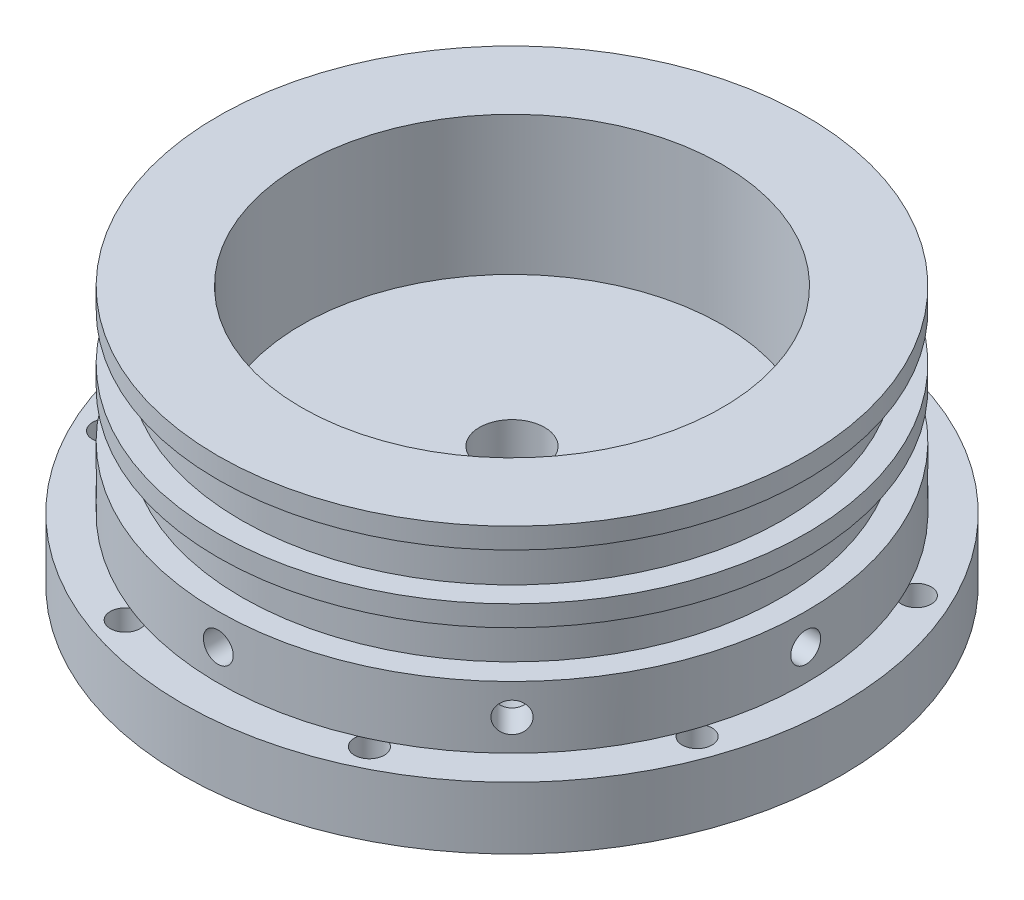
SolidWorks part; units mm, degrees
material "Nylon 101"
ref_plane "Front Plane" through (0, 0, 0) normal (0, 0, 1) x (1, 0, 0)
ref_plane "Top Plane" through (0, 0, 0) normal (0, 1, 0) x (1, 0, 0)
ref_plane "Right Plane" through (0, 0, 0) normal (1, 0, 0) x (0, 0, -1)
sketch "Sketch1" plane through (0, 0, 0) normal (0, 1, 0) x (1, 0, 0)
  circle A0 centre (0, 0) radius 45.085
  dimension "D1" = 90.17
extrude "Boss-Extrude1" add sketch "Sketch1" along normal blind 9.525
sketch "Sketch2" plane through (0, 9.525, 0) normal (0, 1, 0) x (1, 0, 0)
  circle A0 centre (0, 0) radius 41.402
  dimension "D1" = 82.804
extrude "Boss-Extrude2" add sketch "Sketch2" along normal blind 7.1374
sketch "Sketch3" plane through (0, 16.6624, 0) normal (0, 1, 0) x (1, 0, 0)
  circle A0 centre (0, 0) radius 45.085
  dimension "D1" = 90.17
extrude "Boss-Extrude3" add sketch "Sketch3" along normal blind 3.175
sketch "Sketch4" plane through (0, 19.8374, 0) normal (0, 1, 0) x (1, 0, 0)
  circle A0 centre (0, 0) radius 41.529
  dimension "D1" = 83.058
extrude "Boss-Extrude4" add sketch "Sketch4" along normal blind 7.1374
sketch "Sketch5" plane through (0, 26.9748, 0) normal (0, 1, 0) x (1, 0, 0)
  circle A0 centre (0, 0) radius 45.085
  dimension "D1" = 90.17
extrude "Boss-Extrude5" add sketch "Sketch5" along normal blind 3.175
hole_wizard "#15 (0.18) Diameter Hole2" positions "3DSketch1" profile "Sketch6" hole size "#15" standard "ANSI Inch"
sketch3d "3DSketch1"
  line L0 (-45.085, 0, 0) -> (-45.085, 9.525, 0) construction
  circle A0 centre (0, 9.525, 0) radius 45.085 construction
  circle A1 centre (0, 0, 0) radius 45.085 construction
  point P0 (-45.085, 4.7625, 0)
  point P9 (0, 54.61, 0)
  point P14 (0, 45.085, 0)
sketch "Sketch6" plane through (-45.085, 4.7625, 0) normal (0, 1, 0) x (0, 0, 1)
  line L0 (0, 0) -> (0, 6.3736)
  line L1 (0, 6.3736) -> (2.286, 5)
  line L2 (2.286, 5) -> (2.286, 0)
  line L5 (2.286, 0) -> (0, 0)
  line L10 (0, 6.3736) -> (-2.286, 5) construction
  line L11 (0, -6.35) -> (0, 107.95) construction
  dimension "Hole Dia." = 4.572
  dimension "Hole Depth" = 5
  dimension "Drill Angle" = 118
pattern_circular "CirPattern1" count 8 over 360 about axis through (0, 9.525, 0) along (0, -1, 0) of "#15 (0.18) Diameter Hole2"
hole_wizard "M10x1.0 Tapped Hole1" positions "Sketch8" profile "Sketch7" tap size "M10x1.0" standard "ANSI Metric"
sketch "Sketch8" plane through (0, 0, 0) normal (0, -1, 0) x (-1, 0, 0)
  point P0 (0, 0)
sketch "Sketch7" plane through (0, 0, 0) normal (1, 0, 0) x (0, 0, -1)
  line L0 (0, 0) -> (0, 27.7039)
  line L1 (0, 27.7039) -> (4.5, 25)
  line L2 (4.5, 25) -> (4.5, 20)
  line L3 (4.5, 20) -> (5, 20)
  line L4 (5, 20) -> (5, 0)
  line L5 (5, 0) -> (0, 0)
  line L10 (0, 27.7039) -> (-4.5, 25) construction
  line L11 (0, -6.35) -> (0, 107.95) construction
  dimension "Tap Drill Dia." = 9
  dimension "Tap Drill Depth" = 25
  dimension "Thread Major Dia." = 10
  dimension "Thread Depth" = 20
  dimension "Drill Angle" = 118
sketch "Sketch9" plane through (0, 30.1498, 0) normal (0, 1, 0) x (1, 0, 0)
  circle A0 centre (0, 0) radius 40.259 construction
  circle A1 centre (0, 0) radius 32.259
  dimension "D1" = 80.518
  dimension "D2" = 8
extrude "Cut-Extrude1" cut sketch "Sketch9" against normal offset from surface (21.2598 mm away) 8.89 up to face at (0, 0, -5)
sketch "Sketch10" plane through (0, 0, 0) normal (0, -1, 0) x (1, 0, 0)
  line L0 (0, 0) -> (0, -32.385) construction
  line L1 (-6.35, -32.385) -> (6.35, -32.385)
  line L2 (-6.35, -32.385) -> (-6.35, -51.435)
  line L3 (-6.35, -51.435) -> (6.35, -51.435)
  line L4 (6.35, -32.385) -> (6.35, -51.435)
  circle A0 centre (0, 0) radius 45.085 construction
  point P9 (0, 0)
  dimension "D1" = 6.35
  dimension "D2" = 12.7
  dimension "D3" = 19.05
sketch "Sketch11" plane through (0, 0, 0) normal (0, -1, 0) x (-1, 0, 0)
  circle A0 centre (0, 0) radius 50.546
  dimension "D1" = 101.092
extrude "Boss-Extrude6" add sketch "Sketch11" along normal blind 9.525
sketch "Sketch12" plane through (0, -9.525, 0) normal (0, -1, 0) x (1, 0, 0)
  circle A0 centre (0, 0) radius 28.575
  dimension "D1" = 57.15
extrude "Cut-Extrude2" cut sketch "Sketch12" against normal up to surface (9.525 mm away) up to face at (0, 0, 45.085)
hole_wizard "#15 (0.18) Diameter Hole1" positions "3DSketch2" profile "Sketch15" hole size "#15" standard "ANSI Inch"
sketch3d "3DSketch2"
  line L0 (15.4596, -9.525, -43.8381) -> (0, 0, 0) construction
  line L2 (0, 0, 0) -> (0, 0, -44.5211) construction
  point P0 (15.4596, -9.525, -43.8381)
  dimension "D2" = 47.45
  dimension "D1" = 22.5
sketch "Sketch15" plane through (15.4596, -9.525, -43.8381) normal (1, 0, 0) x (0, 0, -1)
  line L0 (0, 0) -> (0, 9.525)
  line L1 (0, 9.525) -> (2.286, 9.525)
  line L2 (2.286, 9.525) -> (2.286, 0)
  line L5 (2.286, 0) -> (0, 0)
  line L11 (0, -6.35) -> (0, 107.95) construction
  dimension "Thru Hole Dia." = 4.572
  dimension "Thru Hole Depth" = 9.525
pattern_circular "CirPattern2" count 8 over 360 about axis through (0, 0, 0) along (0, 1, 0) of "#15 (0.18) Diameter Hole1"
equation "\"D1@Sketch1\"=3.55in"
equation "\"D2@3DSketch2\"=1.75in+3"
